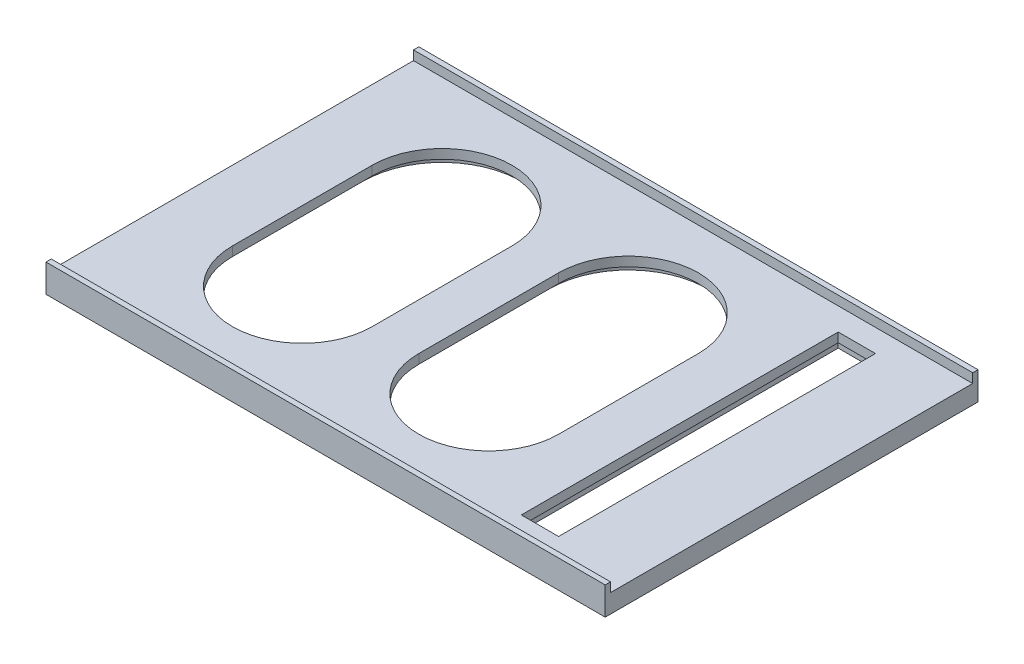
SolidWorks part; units mm, degrees
material "1.4511 (X3CrNb17)"
ref_plane "前视基准面" through (0, 0, 0) normal (0, 0, 1) x (1, 0, 0)
ref_plane "上视基准面" through (0, 0, 0) normal (0, 1, 0) x (1, 0, 0)
ref_plane "右视基准面" through (0, 0, 0) normal (1, 0, 0) x (0, 0, -1)
sketch "草图1" plane through (0, 0, 0) normal (0, 1, 0) x (1, 0, 0)
  line L1 (-300, 200) -> (300, 200)
  line L2 (-300, 200) -> (-300, -200)
  line L3 (-300, -200) -> (300, -200)
  line L4 (300, 200) -> (300, -200)
  line L5 (-300, 200) -> (300, -200) construction
  line L6 (-300, -200) -> (300, 200) construction
  point P0 (0, 0)
  dimension "D1" = 600
  dimension "D2" = 400
extrude "凸台-拉伸1" add sketch "草图1" along normal blind 30
sketch "草图2" plane through (0, 30, 0) normal (0, 1, 0) x (1, 0, 0)
  line L1 (-300, 194.3) -> (300, 194.3)
  line L2 (-300, 194.3) -> (-300, -194.3)
  line L3 (-300, -194.3) -> (300, -194.3)
  line L4 (300, 194.3) -> (300, -194.3)
  line L5 (-300, 194.3) -> (300, -194.3) construction
  line L6 (-300, -194.3) -> (300, 194.3) construction
  point P0 (0, 0)
  dimension "D1" = 600
  dimension "D2" = 388.6
extrude "切除-拉伸1" cut sketch "草图2" against normal blind 10
sketch "草图3" plane through (0, 0, 0) normal (0, -1, 0) x (1, 0, 0)
  line L0 (300, 200) -> (300, -200) construction
  line L1 (175, 175) -> (225, 175)
  line L2 (175, 175) -> (175, -175)
  line L3 (175, -175) -> (225, -175)
  line L4 (225, 175) -> (225, -175)
  line L5 (175, 175) -> (225, -175) construction
  line L6 (175, -175) -> (225, 175) construction
  line L7 (-235, 75) -> (-235, -75)
  line L9 (-35, 75) -> (-35, -75)
  line L11 (135, 75) -> (135, -75)
  line L12 (-35, 75) -> (135, -75) construction
  line L13 (-35, -75) -> (135, 75) construction
  line L14 (-65, 75) -> (-65, -75)
  arc A0 (-35, -75) -> (135, -75) centre (50, -75) ccw
  arc A1 (135, 75) -> (-35, 75) centre (50, 75) ccw
  arc A2 (-235, -75) -> (-65, -75) centre (-150, -75) ccw
  arc A3 (-65, 75) -> (-235, 75) centre (-150, 75) ccw
  point P0 (200, 0)
  point P8 (50, 0)
  dimension "D4" = 85
  dimension "D1" = 50
  dimension "D2" = 350
  dimension "D3" = 100
  dimension "D5" = 150
  dimension "D6" = 150
  dimension "D7" = 2
extrude "切除-拉伸2" cut sketch "草图3" against normal blind 10
sketch "草图4" plane through (0, 10, 0) normal (0, -1, 0) x (1, 0, 0)
  line L0 (300, 200) -> (300, -200) construction
  line L1 (180, 170) -> (220, 170)
  line L2 (180, 170) -> (180, -170)
  line L3 (180, -170) -> (220, -170)
  line L4 (220, 170) -> (220, -170)
  line L5 (180, 170) -> (220, -170) construction
  line L6 (180, -170) -> (220, 170) construction
  line L7 (-225, 75) -> (-225, -75)
  line L9 (-25, 75) -> (-25, -75)
  line L11 (125, 75) -> (125, -75)
  line L12 (-25, 75) -> (125, -75) construction
  line L13 (-25, -75) -> (125, 75) construction
  line L14 (-75, 75) -> (-75, -75)
  arc A0 (-25, -75) -> (125, -75) centre (50, -75) ccw
  arc A1 (125, 75) -> (-25, 75) centre (50, 75) ccw
  arc A2 (-225, -75) -> (-75, -75) centre (-150, -75) ccw
  arc A3 (-75, 75) -> (-225, 75) centre (-150, 75) ccw
  point P0 (200, 0)
  point P8 (50, 0)
  dimension "D4" = 75
  dimension "D1" = 40
  dimension "D2" = 340
  dimension "D3" = 100
  dimension "D5" = 150
  dimension "D6" = 150
  dimension "D7" = 2
extrude "切除-拉伸3" cut sketch "草图4" against normal blind 10
sketch "草图5" plane through (0, 0, 0) normal (0, -1, 0) x (1, 0, 0)
  line L1 (-285, 183.68) -> (285, 183.68) construction
  line L2 (-285, 183.68) -> (-285, -183.68) construction
  line L3 (-285, -183.68) -> (285, -183.68) construction
  line L4 (285, 183.68) -> (285, -183.68) construction
  line L5 (-285, 183.68) -> (285, -183.68) construction
  line L6 (-285, -183.68) -> (285, 183.68) construction
  point P0 (0, 0)
  point P6 (0, 183.68)
  point P7 (0, -183.68)
  dimension "D1" = 570
  dimension "D2" = 367.36
hole_wizard "M6 螺纹孔1" positions "草图6" profile "草图8" tap size "M6" standard "GB"
sketch "草图6" plane through (0, 0, 0) normal (0, -1, 0) x (-1, 0, 0)
  point P0 (285, -183.68)
  point P3 (0, -183.68)
  point P6 (-285, -183.68)
  point P9 (-285, 183.68)
  point P12 (0, 183.68)
  point P15 (285, 183.68)
sketch "草图8" plane through (-285, 0, 183.68) normal (1, 0, 0) x (0, 0, -1)
  line L0 (0, 0) -> (0, 15.5022)
  line L1 (0, 15.5022) -> (2.5, 14)
  line L2 (2.5, 14) -> (2.5, 0)
  line L5 (2.5, 0) -> (0, 0)
  line L10 (0, 15.5022) -> (-2.5, 14) construction
  line L11 (0, -6.35) -> (0, 107.95) construction
  dimension "螺纹孔钻头直径" = 5
  dimension "螺纹孔钻头深度" = 14
  dimension "导头角度" = 118
cosmetic thread "孔螺蚊线1" parameters "D1"=12, "D2"=6
cosmetic thread "孔螺蚊线2" parameters "D1"=12, "D2"=6
cosmetic thread "孔螺蚊线3" parameters "D1"=12, "D2"=6
cosmetic thread "孔螺蚊线4" parameters "D1"=12, "D2"=6
cosmetic thread "孔螺蚊线5" parameters "D1"=12, "D2"=6
cosmetic thread "孔螺蚊线6" parameters "D1"=12, "D2"=6
